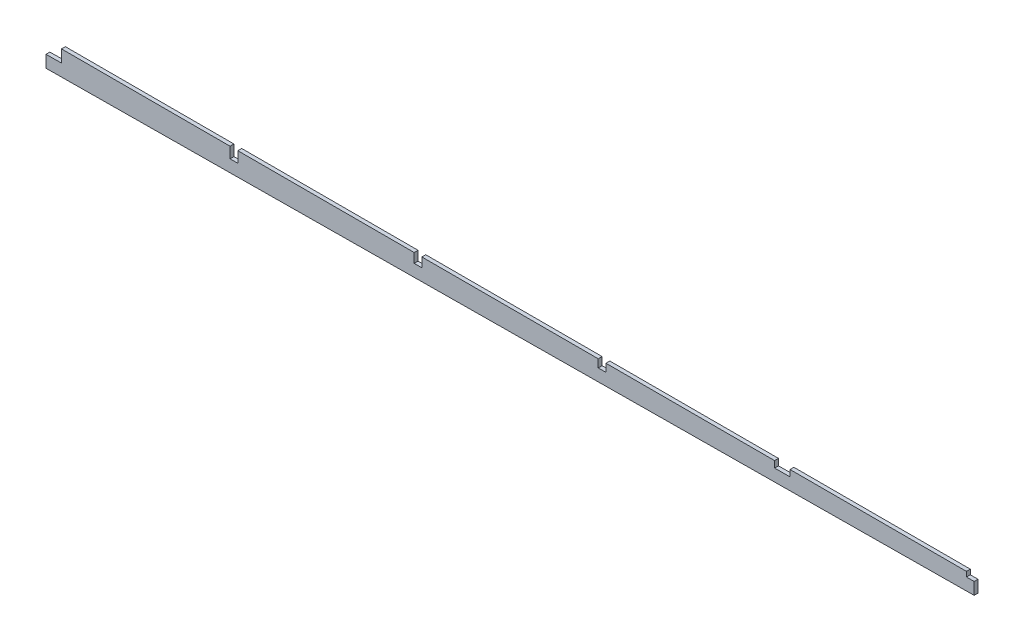
SolidWorks part; units mm, degrees
material "Balsa"
ref_plane "Front Plane" through (0, 0, 0) normal (0, 0, 1) x (1, 0, 0)
ref_plane "Top Plane" through (0, 0, 0) normal (0, 1, 0) x (1, 0, 0)
ref_plane "Right Plane" through (0, 0, 0) normal (1, 0, 0) x (0, 0, -1)
sketch "Sketch2" plane through (0, 0, 1.5875) normal (0, 0, -1) x (-1, 0, 0)
  line L0 (88.3256, -18.9085) -> (88.3256, -13.9358)
  line L1 (88.3256, -13.9358) -> (81.9756, -13.8841)
  line L2 (-292.6744, -10.8379) -> (-292.6744, -15.7932)
  line L3 (-292.6744, -15.7932) -> (88.3256, -18.9085)
  line L4 (-289.4994, -10.8637) -> (-289.4994, -8.8317)
  line L5 (-289.4994, -8.8317) -> (-217.1094, -8.8317)
  line L6 (81.9756, -13.8841) -> (81.9756, -8.8317)
  line L7 (9.5856, -13.2955) -> (9.5856, -8.8317)
  line L8 (12.7606, -13.3213) -> (12.7606, -8.8317)
  line L9 (12.7606, -8.8317) -> (81.9756, -8.8317)
  line L10 (12.7606, -13.3213) -> (9.5856, -13.2955)
  line L11 (-62.8044, -12.7069) -> (-62.8044, -8.8317)
  line L12 (-65.9794, -12.6811) -> (-65.9794, -8.8317)
  line L13 (-138.3694, -12.0925) -> (-138.3694, -8.8317)
  line L14 (-141.5444, -12.0667) -> (-141.5444, -8.8317)
  line L15 (-217.1094, -11.4523) -> (-217.1094, -8.8317)
  line L16 (-210.7594, -11.5039) -> (-210.7594, -8.8317)
  line L17 (-210.7594, -8.8317) -> (-141.5444, -8.8317)
  line L18 (-210.7594, -11.5039) -> (-217.1094, -11.4523)
  line L19 (-138.3694, -12.0925) -> (-141.5444, -12.0667)
  line L20 (-138.3694, -8.8317) -> (-65.9794, -8.8317)
  line L21 (-62.8044, -8.8317) -> (9.5856, -8.8317)
  line L22 (-62.8044, -12.7069) -> (-65.9794, -12.6811)
  line L23 (-289.4994, -10.8637) -> (-292.6744, -10.8379)
  dimension "D1" = 2.032
extrude "Boss-Extrude1" add sketch "Sketch2" along normal up to surface (1.5875 mm away) contours L3 L0 L1 L6 L9 L8 L10 L7 L21 L11 L22 L12 L20 L13 L19 L14 L17 L16 L18 L15 L5 L4 L23 L2
